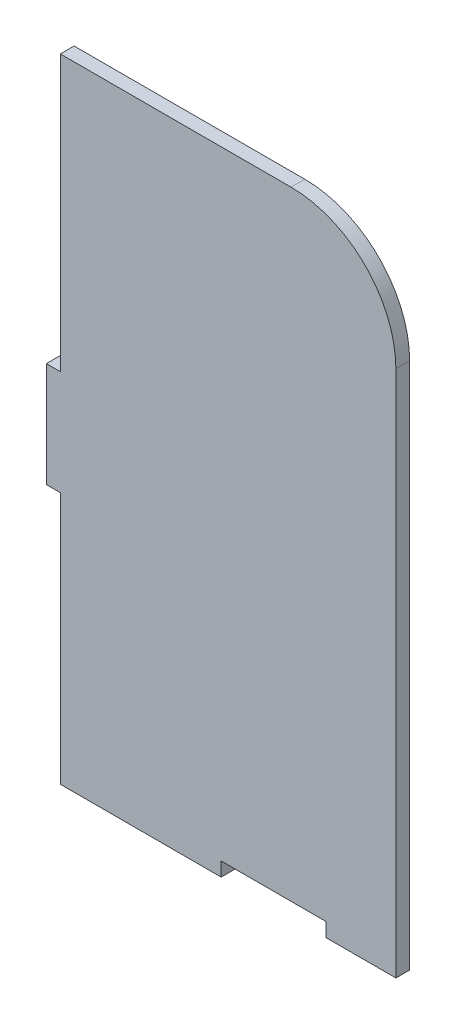
SolidWorks part; units mm, degrees
ref_plane "Front Plane" through (0, 0, 0) normal (0, 0, 1) x (1, 0, 0)
ref_plane "Top Plane" through (0, 0, 0) normal (0, 1, 0) x (1, 0, 0)
ref_plane "Right Plane" through (0, 0, 0) normal (1, 0, 0) x (0, 0, -1)
sketch "Sketch1" plane through (0, 0, 0) normal (0, 0, 1) x (1, 0, 0)
  line L0 (215.8296, -10.16) -> (383.5218, -10.16)
  line L1 (459.7218, -86.36) -> (459.7218, -469.9)
  line L2 (215.8296, -10.16) -> (215.8296, -210.16)
  line L6 (215.8296, -210.16) -> (205.6631, -210.16)
  line L8 (205.6631, -210.16) -> (205.6631, -286.36)
  line L10 (205.6631, -286.36) -> (215.8296, -286.36)
  line L12 (215.8296, -286.36) -> (215.8296, -469.9)
  line L13 (215.8296, -469.9) -> (332.7218, -469.9)
  line L14 (408.9218, -469.9) -> (408.9218, -459.74)
  line L15 (408.9218, -459.74) -> (332.7218, -459.74)
  line L16 (332.7218, -459.74) -> (332.7218, -469.9)
  line L17 (408.9218, -469.9) -> (459.7218, -469.9)
  arc A2 (459.7218, -86.36) -> (383.5218, -10.16) centre (383.5218, -86.36) ccw
  dimension "D1" = 76.2
  dimension "D2" = 200
extrude "Boss-Extrude1" add sketch "Sketch1" against normal blind 10
